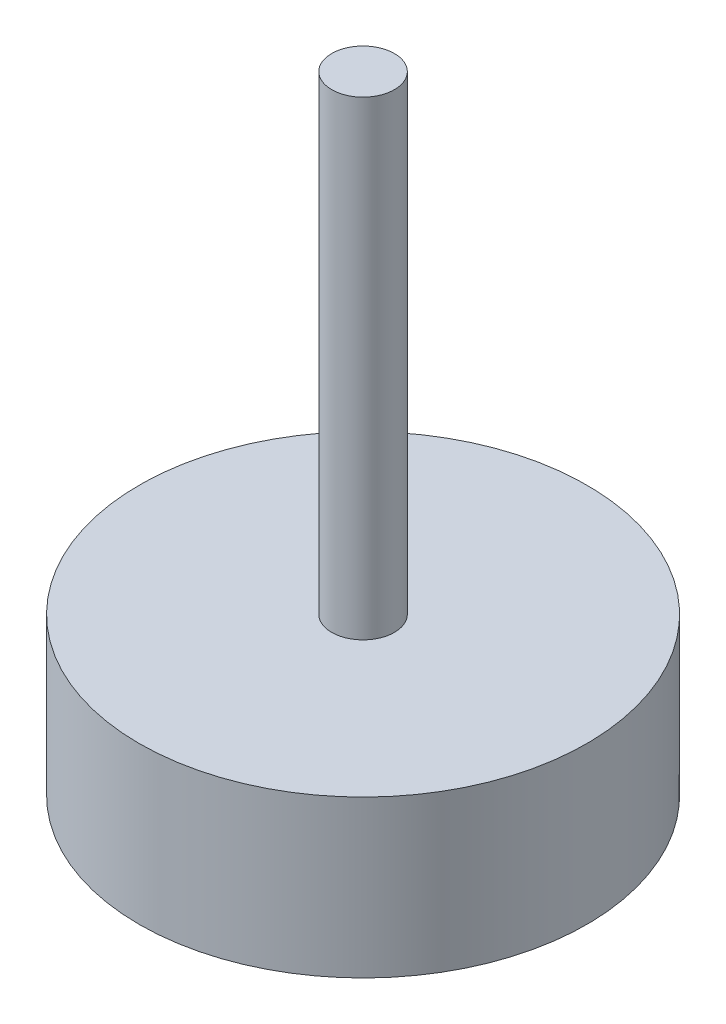
SolidWorks part; units mm, degrees
ref_plane "Plan de face" through (0, 0, 0) normal (0, 0, 1) x (1, 0, 0)
ref_plane "Plan de dessus" through (0, 0, 0) normal (0, 1, 0) x (1, 0, 0)
ref_plane "Plan de droite" through (0, 0, 0) normal (1, 0, 0) x (0, 0, -1)
other "1"
other "2"
sketch "Esquisse1" plane through (0, 0, 0) normal (0, 1, 0) x (1, 0, 0)
  circle A0 centre (0, 0) radius 5
  dimension "D1" = 10
extrude "Boss.-Extru.1" add sketch "Esquisse1" along normal blind 14
sketch "Esquisse2" plane through (0, 14, 0) normal (0, 1, 0) x (1, 0, 0)
  circle A0 centre (0, 0) radius 0.7
  circle A1 centre (0, 0) radius 5
  circle A2 centre (0, 0) radius 5 construction
  dimension "D1" = 1.4
extrude "Enlèv. mat.-Extru.1" cut sketch "Esquisse2" against normal offset from surface (10.5 mm away) 3.5 up to face at (0, 0, 5)
